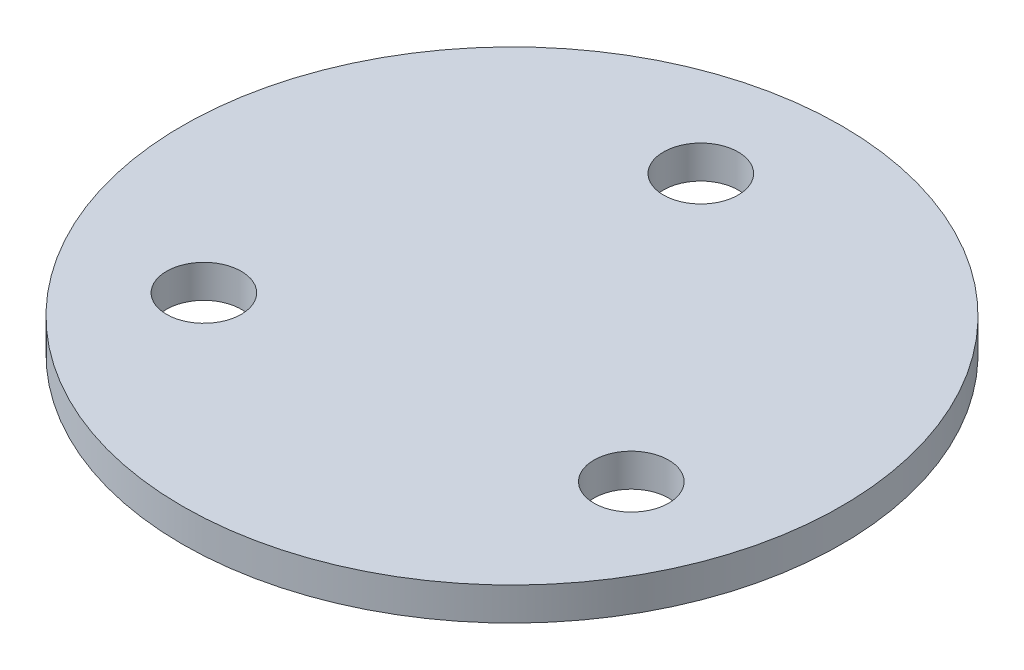
SolidWorks part; units mm, degrees
ref_plane "Front Plane" through (0, 0, 0) normal (0, 0, 1) x (1, 0, 0)
ref_plane "Top Plane" through (0, 0, 0) normal (0, 1, 0) x (1, 0, 0)
ref_plane "Right Plane" through (0, 0, 0) normal (1, 0, 0) x (0, 0, -1)
sketch "Sketch1" plane through (0, 0, 0) normal (0, 1, 0) x (1, 0, 0)
  circle A0 centre (0, 0) radius 15
  circle A1 centre (9.244, -3.8143) radius 1.7
  circle A2 centre (-7.9253, -6.0984) radius 1.7
  circle A3 centre (-1.3187, 9.9127) radius 1.7
  point P8 (0, 0)
  point P9 (0, 0)
  point P10 (0, 0)
  dimension "D1" = 10
extrude "Boss-Extrude1" add sketch "Sketch1" along normal blind 1.5
